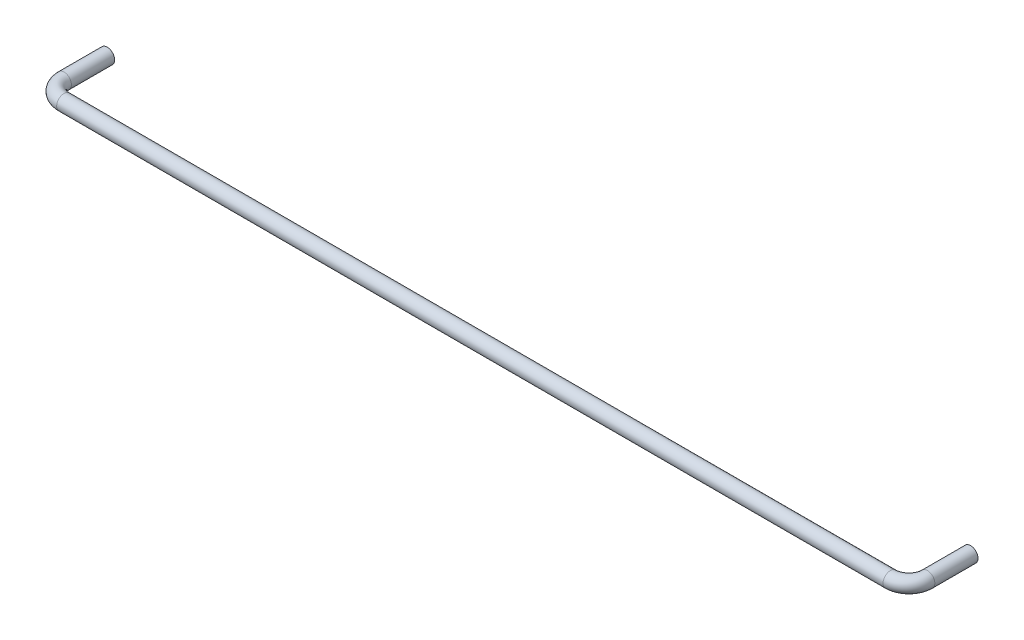
SolidWorks part; units mm, degrees
ref_plane "Front Plane" through (0, 0, 0) normal (0, 0, 1) x (1, 0, 0)
ref_plane "Top Plane" through (0, 0, 0) normal (0, 1, 0) x (1, 0, 0)
ref_plane "Right Plane" through (0, 0, 0) normal (1, 0, 0) x (0, 0, -1)
sketch "Sketch2" plane through (0, 0, 0) normal (0, 1, 0) x (1, 0, 0)
  line L0 (1.5, -5) -> (68.5, -5)
  line L1 (70, -3.5) -> (70, 0)
  line L2 (0, -3.5) -> (0, 0)
  arc A0 (68.5, -5) -> (70, -3.5) centre (68.5, -3.5) ccw
  arc A1 (0, -3.5) -> (1.5, -5) centre (1.5, -3.5) ccw
  point P7 (70, -5)
  point P10 (0, -5)
  dimension "D4" = 1.5
  dimension "D1" = 5
  dimension "D2" = 5
  dimension "D3" = 70
sketch "Sketch3" plane through (0, 0, 0) normal (0, 0, 1) x (1, 0, 0)
  circle A0 centre (0, 0) radius 0.6
  dimension "D1" = 1.2
sweep "Sweep1" add profiles "Sketch3" path "Sketch2"
